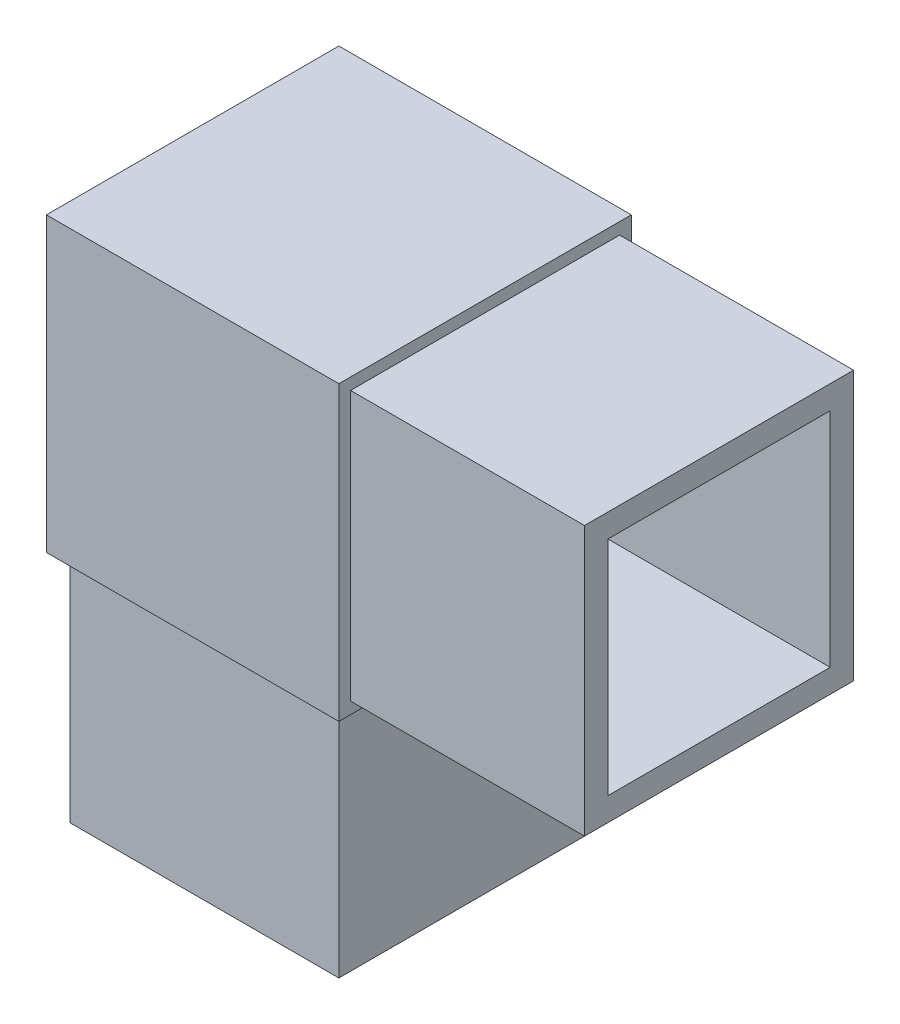
SolidWorks part; units mm, degrees
ref_plane "Front Plane" through (0, 0, 0) normal (0, 0, 1) x (1, 0, 0)
ref_plane "Top Plane" through (0, 0, 0) normal (0, 1, 0) x (1, 0, 0)
ref_plane "Right Plane" through (0, 0, 0) normal (1, 0, 0) x (0, 0, -1)
sketch "Sketch1" plane through (0, 0, 0) normal (0, 0, 1) x (1, 0, 0)
  line L1 (-45.1495, -179.7121) -> (-0.1495, -179.7121)
  line L2 (-45.1495, -179.7121) -> (-45.1495, -134.7121)
  line L3 (-45.1495, -134.7121) -> (-0.1495, -134.7121)
  line L4 (-0.1495, -179.7121) -> (-0.1495, -134.7121)
  dimension "D1" = 45
  dimension "D2" = 45
extrude "Boss-Extrude1" add sketch "Sketch1" along normal blind 25 contours L1 L4 L3 L2
sketch "Sketch2" plane through (0, 0, 25) normal (0, 0, 1) x (1, 0, 0)
  line L1 (-0.1495, -179.7121) -> (-20.1495, -179.7121)
  line L2 (-0.1495, -179.7121) -> (-0.1495, -159.7121)
  line L3 (-0.1495, -159.7121) -> (-20.1495, -159.7121)
  line L4 (-20.1495, -179.7121) -> (-20.1495, -159.7121)
  dimension "D1" = 20
  dimension "D2" = 20
extrude "Cut-Extrude1" cut sketch "Sketch2" against normal through all
sketch "Sketch3" plane through (-0.1495, 0, 0) normal (1, 0, 0) x (0, 0, -1)
  line L0 (-25, -134.7121) -> (0, -134.7121) construction
  line L1 (-25, -159.7121) -> (0, -159.7121)
  line L2 (-25, -159.7121) -> (-25, -134.7121)
  line L3 (-25, -134.7121) -> (0, -134.7121)
  line L4 (0, -159.7121) -> (0, -134.7121)
  line L6 (-24, -158.7121) -> (-1, -158.7121)
  line L7 (-24, -158.7121) -> (-24, -135.7121)
  line L8 (-24, -135.7121) -> (-1, -135.7121)
  line L9 (-1, -158.7121) -> (-1, -135.7121)
  dimension "D1" = 23
  dimension "D2" = 23
  dimension "D3" = 1
  dimension "D4" = 1
extrude "Cut-Extrude2" cut sketch "Sketch3" against normal up to surface (20 mm away) up to face at (-20.1495, -169.7121, 12.5)
sketch "Sketch4" plane through (0, -179.7121, 0) normal (0, -1, 0) x (1, 0, 0)
  line L0 (-45.1495, 25) -> (-45.1495, 0) construction
  line L1 (-44.1495, 24) -> (-21.1495, 24)
  line L2 (-44.1495, 24) -> (-44.1495, 1)
  line L3 (-44.1495, 1) -> (-21.1495, 1)
  line L4 (-21.1495, 24) -> (-21.1495, 1)
  line L5 (-45.1495, 0) -> (-20.1495, 0) construction
  line L7 (-45.1495, 25) -> (-20.1495, 25)
  line L8 (-45.1495, 25) -> (-45.1495, 0)
  line L9 (-45.1495, 0) -> (-20.1495, 0)
  line L10 (-20.1495, 25) -> (-20.1495, 0)
  dimension "D1" = 23
  dimension "D2" = 23
  dimension "D3" = 1
  dimension "D4" = 1
extrude "Cut-Extrude3" cut sketch "Sketch4" against normal blind 20
sketch "Sketch7" plane through (-0.1495, 0, 0) normal (1, 0, 0) x (0, 0, -1)
  line L0 (-24, -158.7121) -> (-1, -158.7121) construction
  line L1 (-22, -156.7121) -> (-3, -156.7121)
  line L2 (-22, -156.7121) -> (-22, -137.7121)
  line L3 (-22, -137.7121) -> (-3, -137.7121)
  line L4 (-3, -156.7121) -> (-3, -137.7121)
  line L5 (-24, -135.7121) -> (-24, -158.7121) construction
  dimension "D1" = 19
  dimension "D2" = 19
  dimension "D3" = 2
  dimension "D4" = 2
sketch "Sketch8" plane through (0, -179.7121, 0) normal (0, -1, 0) x (1, 0, 0)
  line L0 (-21.1495, 24) -> (-44.1495, 24) construction
  line L1 (-42.1495, 22) -> (-23.1495, 22)
  line L2 (-42.1495, 22) -> (-42.1495, 3)
  line L3 (-42.1495, 3) -> (-23.1495, 3)
  line L4 (-23.1495, 22) -> (-23.1495, 3)
  line L5 (-44.1495, 24) -> (-44.1495, 1) construction
  dimension "D1" = 2
  dimension "D2" = 2
  dimension "D3" = 19
  dimension "D4" = 19
extrude "Cut-Extrude7" cut sketch "Sketch7" against normal blind 42
extrude "Cut-Extrude8" cut sketch "Sketch8" against normal up to surface (42 mm away) up to face at (-21.1495, -137.7121, 12.5)
